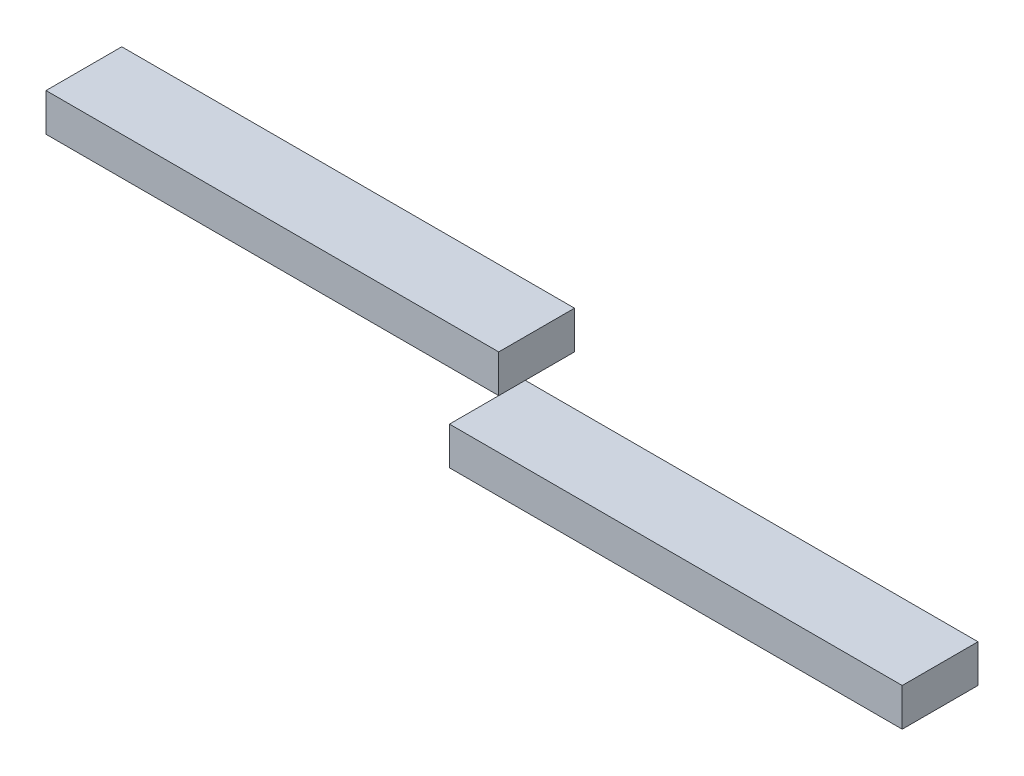
SolidWorks part; units mm, degrees
ref_plane "Front Plane" through (0, 0, 0) normal (0, 0, 1) x (1, 0, 0)
ref_plane "Top Plane" through (0, 0, 0) normal (0, 1, 0) x (1, 0, 0)
ref_plane "Right Plane" through (0, 0, 0) normal (1, 0, 0) x (0, 0, -1)
sketch "Sketch1" plane through (0, 0, 0) normal (0, 1, 0) x (1, 0, 0)
  line L0 (-26.5601, 9.4428) -> (-56.9131, 9.4428)
  line L1 (-26.5601, 9.4428) -> (-26.5601, 14.5228)
  line L2 (-26.5601, 14.5228) -> (-56.9131, 14.5228)
  line L3 (-56.9131, 9.4428) -> (-56.9131, 14.5228)
  line L4 (-24.0201, 8.6808) -> (6.3329, 8.6808)
  line L5 (-24.0201, 8.6808) -> (-24.0201, 3.6008)
  line L6 (-24.0201, 3.6008) -> (6.3329, 3.6008)
  line L7 (6.3329, 8.6808) -> (6.3329, 3.6008)
extrude "Boss-Extrude1" add sketch "Sketch1" along normal blind 2.54
